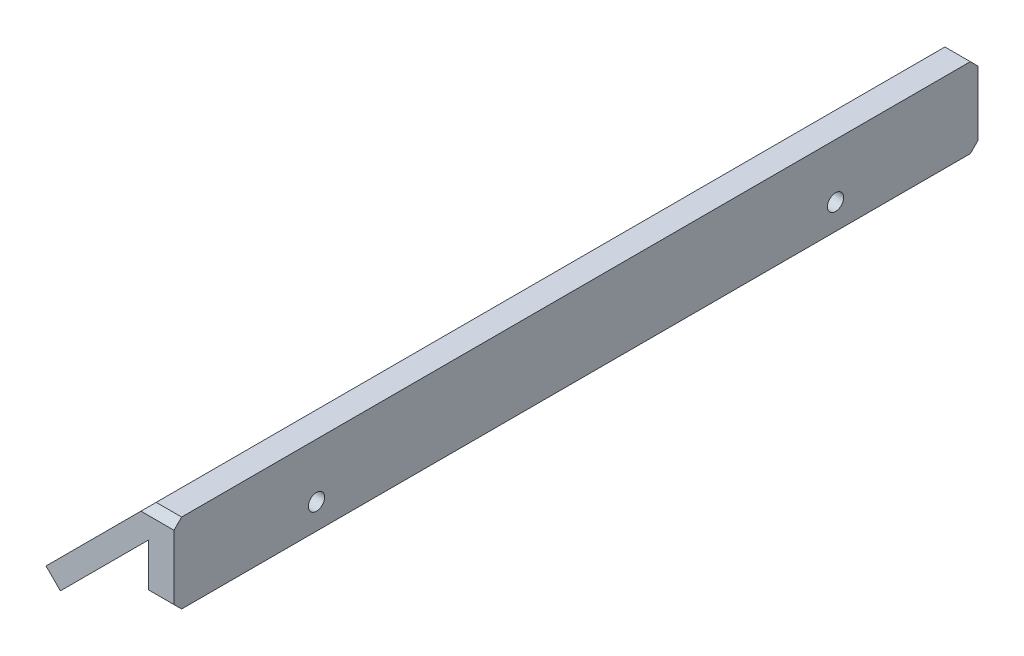
SolidWorks part; units mm, degrees
ref_plane "前视基准面" through (0, 0, 0) normal (0, 0, 1) x (1, 0, 0)
ref_plane "上视基准面" through (0, 0, 0) normal (0, 1, 0) x (1, 0, 0)
ref_plane "右视基准面" through (0, 0, 0) normal (1, 0, 0) x (0, 0, -1)
other "Configuration Table"
sketch "草图1" plane through (0, 0, 0) normal (0, 0, 1) x (1, 0, 0)
  line L0 (-43.8052, 53.2278) -> (-48.8052, 53.2278)
  line L4 (-48.8052, 47.5709) -> (-48.8052, 37.5709)
  line L5 (-48.8052, 37.5709) -> (-43.8052, 37.5709)
  line L6 (-43.8052, 37.5709) -> (-43.8052, 53.2278)
  line L7 (-48.8052, 53.2278) -> (-70.0184, 32.0146)
  line L8 (-70.0184, 32.0146) -> (-67.19, 29.1861)
  line L9 (-67.19, 29.1861) -> (-48.8052, 47.5709)
extrude "凸台-拉伸1" add sketch "草图1" along normal blind 158
sketch "草图2" plane through (-43.8052, 0, 0) normal (1, 0, 0) x (0, 0, -1)
  circle A0 centre (-130, 42.5709) radius 1.6
  circle A1 centre (-28, 42.5709) radius 1.6
extrude "切除-拉伸1" cut sketch "草图2" against normal blind 27
sketch "草图6" plane through (-48.8052, 0, 0) normal (-1, 0, 0) x (0, 0, 1)
  circle A0 centre (130, 42.5709) radius 3.5
  circle A1 centre (28, 42.5709) radius 3.5
extrude "切除-拉伸2" cut sketch "草图6" along normal blind 21
sketch "草图7" plane through (-51.0165, 51.0165, 0) normal (-0.7071, 0.7071, 0) x (0.7071, 0.7071, 0)
  circle A0 centre (-11.8728, -148) radius 2.2
  circle A1 centre (-11.8728, -10) radius 2.2
extrude "切除-拉伸3" cut sketch "草图7" against normal blind 5
sketch "草图8" plane through (-43.8052, 0, 0) normal (1, 0, 0) x (0, 0, -1)
  line L0 (-158, 53.2278) -> (-158, 51.7278)
  line L1 (-158, 53.2278) -> (0, 53.2278) construction
  line L2 (-158, 37.5709) -> (-158, 53.2278) construction
  line L3 (-158, 53.2278) -> (-156.5, 53.2278)
  line L4 (-156.5, 53.2278) -> (-158, 51.7278)
  line L5 (0, 53.2278) -> (-1.5, 53.2278)
  line L6 (-158, 39.0709) -> (-158, 37.5709)
  line L7 (-158, 37.5709) -> (-156.5, 37.5709)
  line L8 (-158, 37.5709) -> (0, 37.5709) construction
  line L9 (-156.5, 37.5709) -> (-158, 39.0709)
  line L10 (0, 53.2278) -> (0, 51.7278)
  line L11 (0, 37.5709) -> (0, 53.2278) construction
  line L12 (0, 51.7278) -> (-1.5, 53.2278)
  line L13 (0, 37.5709) -> (0, 39.0709)
  line L14 (0, 37.5709) -> (-1.5, 37.5709)
  line L15 (-1.5, 37.5709) -> (0, 39.0709)
extrude "切除-拉伸4" cut sketch "草图8" against normal blind 10
sketch "草图9" plane through (-48.188, 48.188, 0) normal (0.7071, -0.7071, 0) x (0, 0, -1)
  line L0 (-158, -26.8728) -> (-158, -25.3728)
  line L1 (-158, -26.8728) -> (-158, -0.8728) construction
  line L2 (-158, -26.8728) -> (-156.5, -26.8728)
  line L3 (-158, -26.8728) -> (0, -26.8728) construction
  line L4 (-156.5, -26.8728) -> (-158, -25.3728)
  line L5 (0, -26.8728) -> (0, -25.3728)
  line L6 (0, -26.8728) -> (0, -0.8728) construction
  line L7 (0, -26.8728) -> (-1.5, -26.8728)
  line L8 (-1.5, -26.8728) -> (0, -25.3728)
extrude "切除-拉伸5" cut sketch "草图9" against normal blind 4
